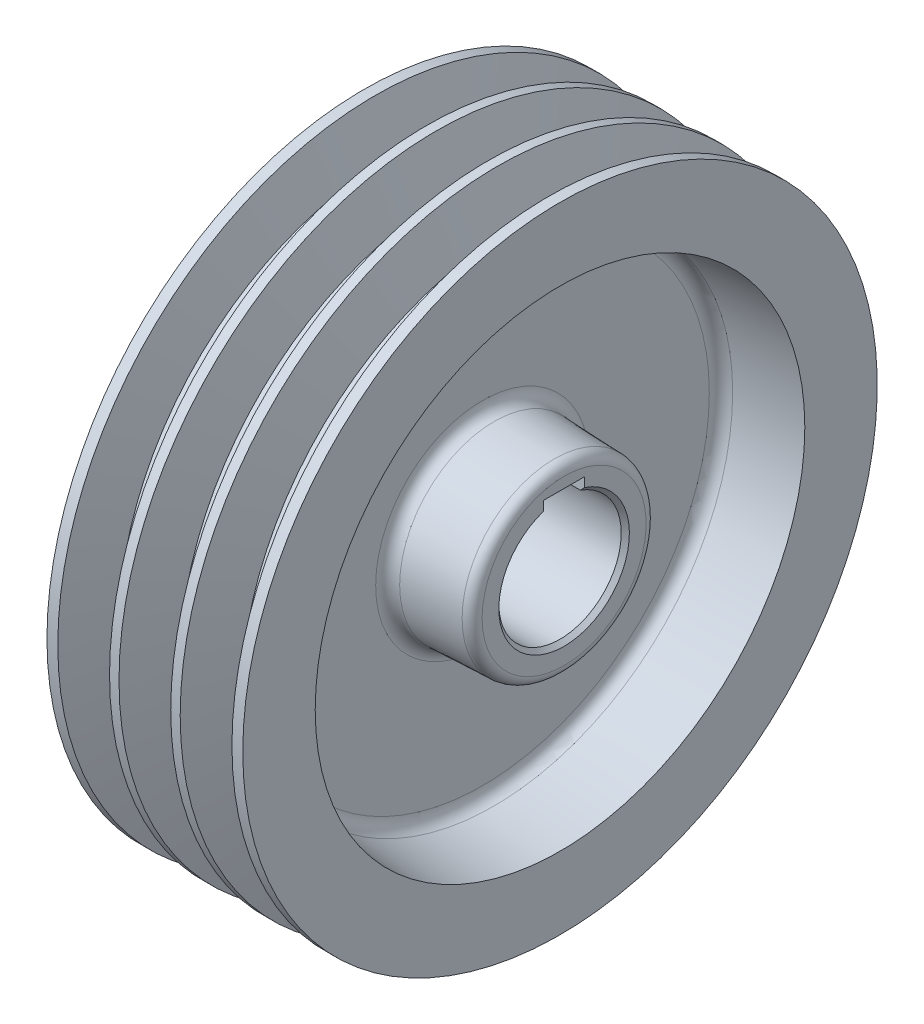
SolidWorks part; units mm, degrees
ref_plane "前视基准面" through (0, 0, 0) normal (0, 0, 1) x (1, 0, 0)
ref_plane "上视基准面" through (0, 0, 0) normal (0, 1, 0) x (1, 0, 0)
ref_plane "右视基准面" through (0, 0, 0) normal (1, 0, 0) x (0, 0, -1)
sketch "草图1" plane through (0, 0, 0) normal (0, 0, 1) x (1, 0, 0)
  line L0 (0, 0) -> (64.8368, 0) construction
  line L1 (-1, 15) -> (-1, 22.5)
  line L2 (0, 77.75) -> (48, 77.75)
  line L3 (48, 77.75) -> (48, 60)
  line L4 (-1, 22.5) -> (-30, 22.5) construction
  line L5 (19, 24.2498) -> (19, 59.2402)
  line L6 (49, 15) -> (-1, 15)
  line L7 (2.6592, 77.75) -> (6.1599, 66.3) construction
  line L8 (6.1599, 66.3) -> (11.8401, 66.3) construction
  line L9 (11.8401, 66.3) -> (15.3408, 77.75) construction
  line L10 (0, 75) -> (48, 75) construction
  line L11 (9, 66.3) -> (9, 15) construction
  line L12 (44, 60) -> (0, 60) construction
  line L13 (48, 60) -> (79, 60) construction
  line L14 (29, 58.3377) -> (29, 23.2998)
  line L15 (5, 22.5) -> (49, 22.5) construction
  line L16 (24, 15) -> (24, 77.75) construction
  line L17 (49, 22.5) -> (49, 15)
  line L18 (0, 60) -> (0, 77.75)
  line L19 (19, 51) -> (29, 51) construction
  line L20 (19, 31.5) -> (29, 31.5) construction
  line L21 (48, 60) -> (48, 51) construction
  line L22 (48, 51) -> (29, 51) construction
  line L23 (29, 31.5) -> (49, 31.5) construction
  line L24 (49, 31.5) -> (49, 22.5) construction
  line L25 (29, 58.3377) -> (48, 60)
  line L26 (19, 59.2402) -> (0, 60)
  line L27 (19, 24.2498) -> (-1, 22.5)
  line L28 (29, 23.2998) -> (49, 22.5)
  point P17 (3.5, 75)
  point P18 (14.5, 75)
  dimension "d2" = 120
  dimension "L" = 50
  dimension "B" = 48
  dimension "d" = 30
  dimension "d1" = 45
  dimension "D3" = 5
  dimension "D4" = 2.29
  dimension "dd" = 150
  dimension "f" = 9
  dimension "槽轮角" = 34
  dimension "bd" = 11
  dimension "hf" = 8.7
  dimension "ha" = 2.75
  dimension "da" = 155.5
  dimension "S" = 10
  dimension "S2" = 9
revolve "旋转1" add sketch "草图1" angle 360 about L0
sketch "草图2" plane through (0, 0, 0) normal (0, 0, 1) x (1, 0, 0)
  line L0 (11.8401, 66.3) -> (15.3408, 77.75) construction
  line L1 (6.1599, 66.3) -> (11.8401, 66.3) construction
  line L2 (2.6592, 77.75) -> (6.1599, 66.3) construction
  line L3 (11.8401, 66.3) -> (15.3408, 77.75)
  line L4 (6.1599, 66.3) -> (11.8401, 66.3)
  line L5 (2.6592, 77.75) -> (6.1599, 66.3)
  line L6 (2.6592, 77.75) -> (15.3408, 77.75)
  line L7 (0, 0) -> (123, 0) construction
revolve "切除-旋转1" cut sketch "草图2" angle 360 about L7
pattern_linear "轮槽数" count 3 spacing 15 along (1, 0, 0) of "切除-旋转1"
chamfer "倒角1" distance 1 2 edges at (-1, 0, 15) (49, 0, 15)
sketch "草图4" plane through (-1, 0, 0) normal (-1, 0, 0) x (0, 0, 1)
  line L1 (-5, 14.1421) -> (5, 14.1421)
  line L2 (-5, 14.1421) -> (-5, 17.5)
  line L3 (-5, 17.5) -> (5, 17.5)
  line L4 (5, 14.1421) -> (5, 17.5)
  circle A0 centre (0, 0) radius 15 construction
  point P6 (2.5, 17.5)
  dimension "键槽高度" = 17.5
  dimension "键槽宽度" = 10
  dimension "t1" = 2.5
extrude "切除-拉伸1" cut sketch "草图4" against normal through all
fillet "圆角1" radius 3 4 edges at (29, 0, 58.3377) (19, 0, 24.2498) (19, 0, 59.2402) (29, 0, 23.2998)
fillet "圆角2" radius 2.5 2 edges at (49, 0, 22.5) (-1, 0, 22.5)
equation "\"B@草图1\" =  ( \"z@轮槽数\" - 1 )  * \"e@轮槽数\" +2 *  \"f@草图1\""
equation "\"键槽高度@草图4\" = \"d@草图1\" / 2 + \"t1@草图4\""
